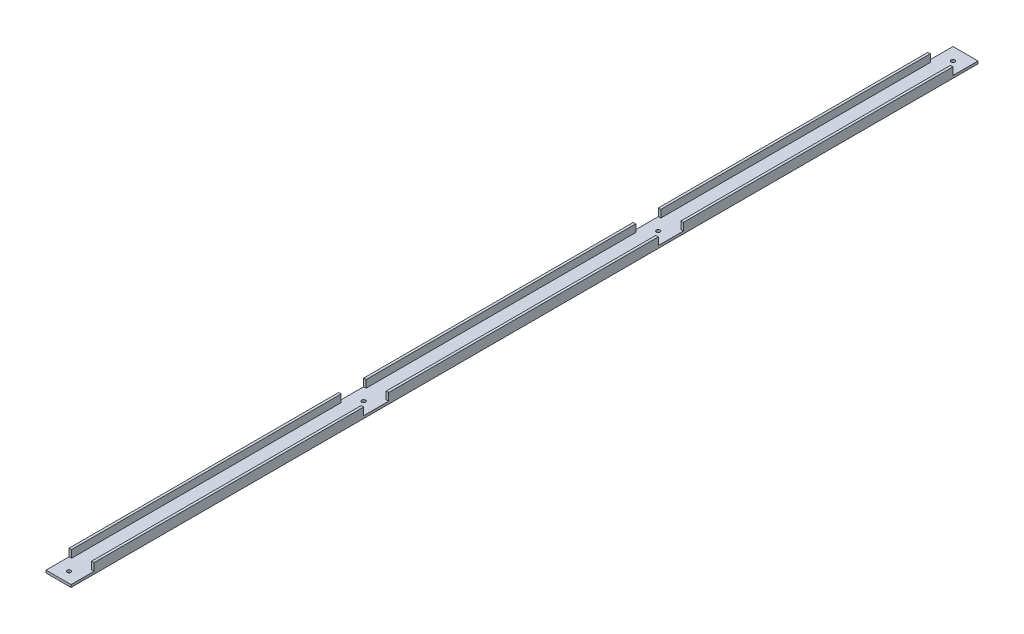
SolidWorks part; units mm, degrees
ref_plane "Front Plane" through (0, 0, 0) normal (0, 0, 1) x (1, 0, 0)
ref_plane "Top Plane" through (0, 0, 0) normal (0, 1, 0) x (1, 0, 0)
ref_plane "Right Plane" through (0, 0, 0) normal (1, 0, 0) x (0, 0, -1)
sketch "Sketch1" plane through (0, 0, 0) normal (0, 0, 1) x (1, 0, 0)
  line L0 (3.175, 3.175) -> (3.175, 12.7)
  line L1 (0, 0) -> (31.75, 0)
  line L2 (0, 0) -> (0, 12.7)
  line L4 (31.75, 0) -> (31.75, 12.7)
  line L5 (3.175, 3.175) -> (28.575, 3.175)
  line L6 (28.575, 3.175) -> (28.575, 12.7)
  line L7 (0, 12.7) -> (3.175, 12.7)
  line L8 (31.75, 12.7) -> (28.575, 12.7)
  dimension "D1" = 31.75
  dimension "D2" = 12.7
  dimension "D3" = 3.175
extrude "Boss-Extrude1" add sketch "Sketch1" along normal blind 1149.35
sketch "Sketch2" plane through (0, 3.175, 0) normal (0, 1, 0) x (1, 0, 0)
  line L0 (28.575, 0) -> (3.175, 0) construction
  line L1 (-61.2758, 55.2903) -> (71.0472, 55.2903)
  line L2 (-61.2758, 55.2903) -> (-61.2758, -31.75)
  line L3 (-61.2758, -31.75) -> (71.0472, -31.75)
  line L4 (71.0472, 55.2903) -> (71.0472, -31.75)
  line L5 (-61.2758, 55.2903) -> (71.0472, -31.75) construction
  line L6 (-61.2758, -31.75) -> (71.0472, 55.2903) construction
  point P4 (4.8857, 11.7701)
  dimension "D1" = 31.75
extrude "Cut-Extrude1" cut sketch "Sketch2" along normal up to next
sketch "Sketch3" plane through (0, 0, 0) normal (-1, 0, 0) x (0, 0, 1)
  line L0 (373.38, 15.875) -> (405.13, 15.875)
  line L8 (373.38, 15.875) -> (373.38, 3.175)
  line L9 (373.38, 3.175) -> (405.13, 3.175)
  line L10 (405.13, 3.175) -> (405.13, 15.875)
  line L11 (405.13, 15.875) -> (401.955, 15.875)
  line L12 (401.955, 15.875) -> (401.955, 6.35)
  line L13 (401.955, 6.35) -> (376.555, 6.35)
  line L14 (376.555, 6.35) -> (376.555, 15.875)
  line L15 (376.555, 15.875) -> (373.38, 15.875)
  line L16 (373.38, 15.875) -> (373.38, 3.175)
  line L17 (373.38, 3.175) -> (405.13, 3.175)
  line L18 (405.13, 3.175) -> (405.13, 15.875)
  dimension "D1" = 0
extrude "Cut-Extrude2" cut sketch "Sketch3" against normal through all
sketch "Sketch4" plane through (0, 0, 0) normal (-1, 0, 0) x (0, 0, 1)
  line L0 (746.76, 15.875) -> (778.51, 15.875)
  line L8 (746.76, 15.875) -> (746.76, 3.175)
  line L9 (746.76, 3.175) -> (778.51, 3.175)
  line L10 (778.51, 3.175) -> (778.51, 15.875)
  line L11 (778.51, 15.875) -> (775.335, 15.875)
  line L12 (775.335, 15.875) -> (775.335, 6.35)
  line L13 (775.335, 6.35) -> (749.935, 6.35)
  line L14 (749.935, 6.35) -> (749.935, 15.875)
  line L15 (749.935, 15.875) -> (746.76, 15.875)
  line L16 (746.76, 15.875) -> (746.76, 3.175)
  line L17 (746.76, 3.175) -> (778.51, 3.175)
  line L18 (778.51, 3.175) -> (778.51, 15.875)
  dimension "D1" = 0
extrude "Cut-Extrude3" cut sketch "Sketch4" against normal through all
sketch "Sketch5" plane through (0, 0, 0) normal (-1, 0, 0) x (0, 0, 1)
  line L0 (1120.14, 15.875) -> (1151.89, 15.875)
  line L8 (1120.14, 15.875) -> (1120.14, 3.175)
  line L9 (1120.14, 3.175) -> (1151.89, 3.175)
  line L10 (1151.89, 3.175) -> (1151.89, 15.875)
  line L11 (1151.89, 15.875) -> (1148.715, 15.875)
  line L12 (1148.715, 15.875) -> (1148.715, 6.35)
  line L13 (1148.715, 6.35) -> (1123.315, 6.35)
  line L14 (1123.315, 6.35) -> (1123.315, 15.875)
  line L15 (1123.315, 15.875) -> (1120.14, 15.875)
  line L16 (1120.14, 15.875) -> (1120.14, 3.175)
  line L17 (1120.14, 3.175) -> (1151.89, 3.175)
  line L18 (1151.89, 3.175) -> (1151.89, 15.875)
  dimension "D1" = 0
extrude "Cut-Extrude4" cut sketch "Sketch5" against normal through all
sketch "Sketch6" plane through (0, 3.175, 0) normal (0, 1, 0) x (1, 0, 0)
  circle A0 centre (15.875, -15.875) radius 2.413 construction
  circle A1 centre (15.875, -15.875) radius 2.413
  circle A2 centre (15.875, -389.255) radius 2.413 construction
  circle A3 centre (15.875, -389.255) radius 2.413
  circle A4 centre (15.875, -762.635) radius 2.413 construction
  circle A5 centre (15.875, -762.635) radius 2.413
  circle A6 centre (15.875, -1136.015) radius 2.413 construction
  circle A7 centre (15.875, -1136.015) radius 2.413
extrude "Cut-Extrude5" cut sketch "Sketch6" against normal up to next
